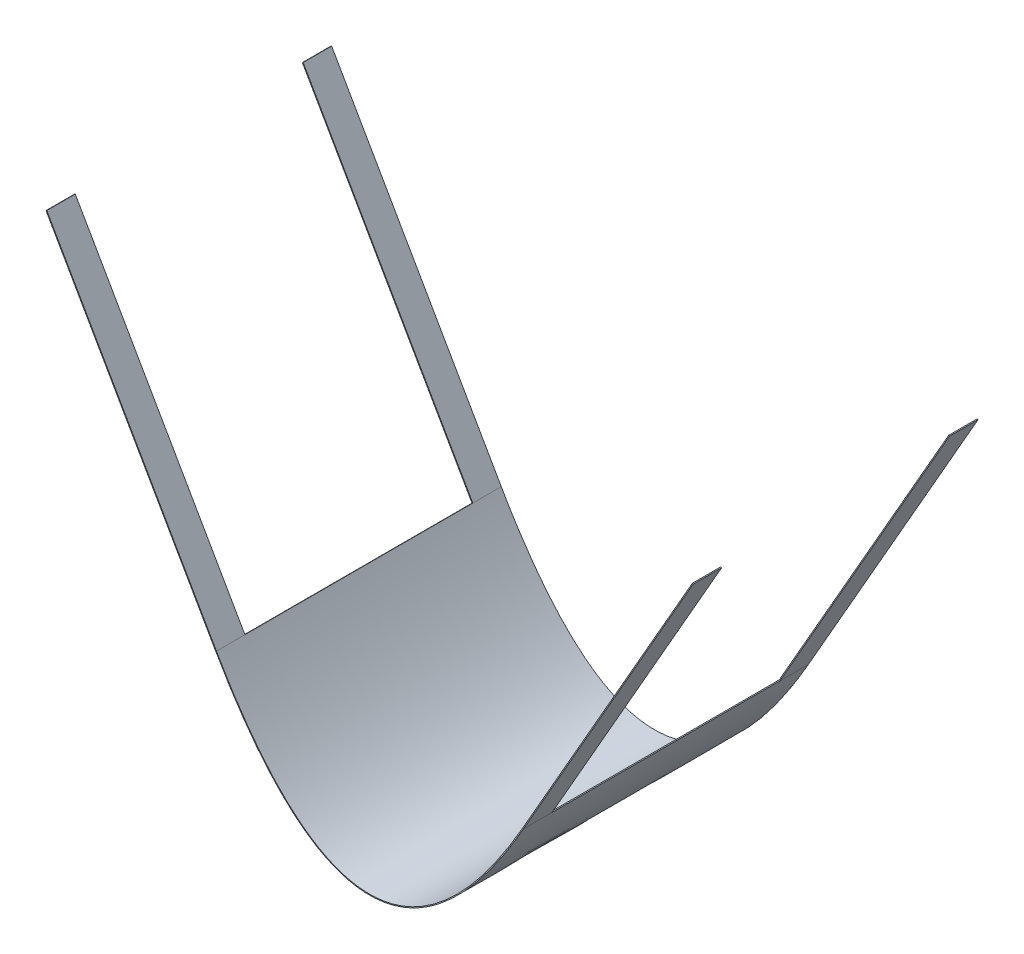
SolidWorks part; units mm, degrees
ref_plane "Front Plane" through (0, 0, 0) normal (0, 0, 1) x (1, 0, 0)
ref_plane "Top Plane" through (0, 0, 0) normal (0, 1, 0) x (1, 0, 0)
ref_plane "Right Plane" through (0, 0, 0) normal (1, 0, 0) x (0, 0, -1)
sketch "Sketch1" plane through (0, 0, 0) normal (0, 0, 1) x (1, 0, 0)
  line L0 (-134.4321, 117.5872) -> (0, -117.5872) construction
  line L1 (0, -117.5872) -> (134.4321, 117.5872) construction
  line L2 (-134.4321, 117.5872) -> (-134.4321, 0) construction
  line L3 (-135.1212, 117.1933) -> (-134.4321, 117.5872)
  line L4 (134.4321, 117.5872) -> (135.1212, 117.1933)
  line L5 (-134.4321, 117.5872) -> (134.4321, 117.5872) construction
  line L6 (0, 0) -> (0, 117.5872) construction
  line L7 (0, 47.5143) -> (-85.4545, 47.5143) construction
  spline S0 degree 2 poles (-134.4321, 117.5872) (0, -117.5872) (134.4321, 117.5872) knots 0 0 0 1 1 1
  spline S1 degree 1 poles (-135.1212, 117.1933) (135.1212, 117.1933) knots 0 0 1 1 construction
  spline S2 degree 2 poles (-135.1212, 117.1933) (-109.8884, 73.0439) (-67.7509, 26.965) (-33.943, 4.7769) (0, -2.6506) (33.943, 4.7769) (67.7509, 26.965) (109.8884, 73.0439) (135.1212, 117.1933) knots 0 0 0 0.1875 0.3125 0.4375 0.5625 0.6875 0.8125 1 1 1
  dimension "D2" = 0.7937
extrude "Sheet" add sketch "Sketch1" along normal mid plane 250
sketch "Sketch2" plane through (-83.7702, 146.5469, 0) normal (-0.4963, 0.8682, 0) x (0.8682, 0.4963, 0)
  line L0 (-59.1486, -125) -> (-59.1486, 125) construction
  line L1 (-58.3549, 125) -> (-59.1486, 125)
  line L2 (-58.3549, 125) -> (-58.3549, 100)
  line L3 (-58.3549, 100) -> (-59.1486, 100)
  line L4 (-59.1486, 125) -> (-59.1486, 100)
  dimension "D1" = 25
extrude "Legs" add sketch "Sketch2" along normal blind 300
mirror "Mirror1" about plane through (0, 0, 0) normal (1, 0, 0) of "Legs"
mirror "Mirror2" about plane through (0, 0, 0) normal (0, 0, 1) of "Mirror1", "Legs"
